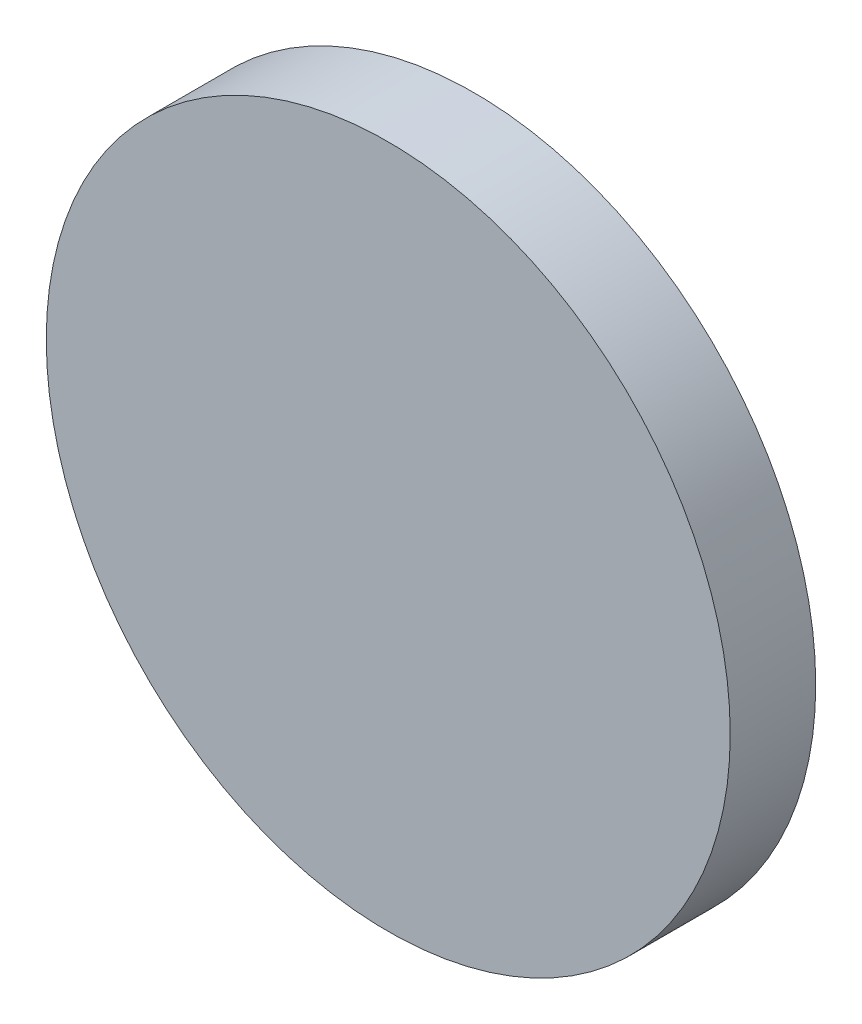
SolidWorks part; units mm, degrees
ref_plane "Front Plane" through (0, 0, 0) normal (0, 0, 1) x (1, 0, 0)
ref_plane "Top Plane" through (0, 0, 0) normal (0, 1, 0) x (1, 0, 0)
ref_plane "Right Plane" through (0, 0, 0) normal (1, 0, 0) x (0, 0, -1)
sketch "Sketch1" plane through (0, 0, 0) normal (0, 0, 1) x (1, 0, 0)
  circle A0 centre (0, 0) radius 40
  dimension "D1" = 80
extrude "Boss-Extrude1" add sketch "Sketch1" along normal blind 10
